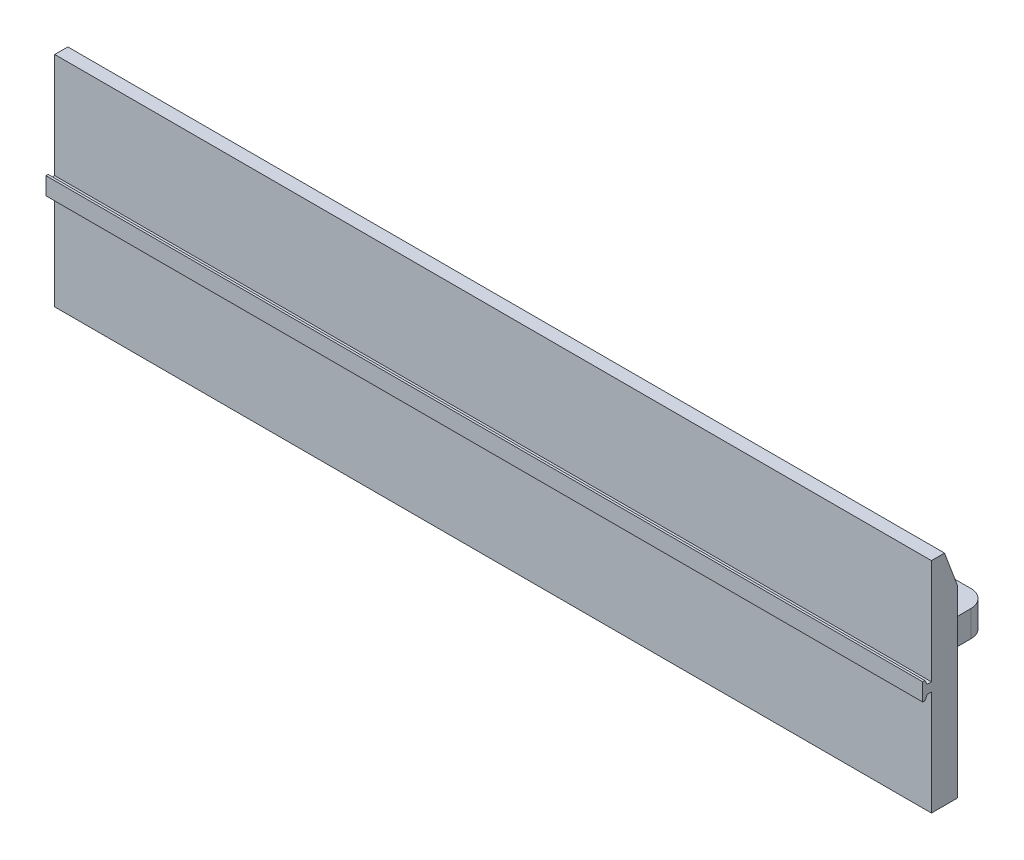
SolidWorks part; units mm, degrees
ref_plane "前视基准面" through (0, 0, 0) normal (0, 0, 1) x (1, 0, 0)
ref_plane "上视基准面" through (0, 0, 0) normal (0, 1, 0) x (1, 0, 0)
ref_plane "右视基准面" through (0, 0, 0) normal (1, 0, 0) x (0, 0, -1)
other "Configuration Table"
sketch "草图1" plane through (1027.5, 0, 0) normal (1, 0, 0) x (0, 0, -1)
  line L0 (-105, 300) -> (-105, 180)
  line L1 (-105, 180) -> (-110, 180)
  line L2 (-110, 180) -> (-112.5, 185)
  line L3 (-112.5, 185) -> (-115, 185)
  line L4 (-115, 185) -> (-115, 165)
  line L5 (-115, 165) -> (-112.5, 165)
  line L6 (-112.5, 165) -> (-110, 170)
  line L7 (-110, 170) -> (-105, 170)
  line L8 (-105, 170) -> (-105, 50)
  line L9 (-105, 300) -> (-90, 300)
  line L10 (-90, 300) -> (-75, 260)
  line L11 (-75, 260) -> (-75, 80)
  line L13 (-75, 50) -> (-105, 50)
  line L15 (-75, 50) -> (110, 50)
  line L17 (-75, 80) -> (110, 80)
  line L18 (110, 50) -> (110, 80)
extrude "凸台-拉伸1" add sketch "草图1" against normal blind 1002.5
sketch "草图2" plane through (0, 80, 0) normal (0, 1, 0) x (1, 0, 0)
  line L0 (25, -115) -> (1027.5, -115) construction
  line L1 (526.25, 145.125) -> (526.25, -305.1005) construction
  line L2 (25, 110) -> (1027.5, 110) construction
  line L3 (326.25, 110) -> (726.25, 110)
  line L4 (326.25, 110) -> (326.25, -75)
  line L5 (326.25, -75) -> (726.25, -75)
  line L6 (726.25, 110) -> (726.25, -75)
  line L7 (25, -75) -> (1027.5, -75) construction
  dimension "D1" = 200
  dimension "D2" = 200
extrude "切除-拉伸1" cut sketch "草图2" against normal through all both and the other way through all
sketch "草图3" plane through (0, 80, 0) normal (0, 1, 0) x (1, 0, 0)
  line L0 (25, -75) -> (1027.5, -75) construction
  line L1 (25, 110) -> (175, 110)
  line L2 (25, 110) -> (25, -75)
  line L3 (25, -75) -> (175, -75)
  line L4 (175, 110) -> (175, -75)
  line L5 (726.25, -75) -> (1027.5, -75) construction
  line L6 (1027.5, 110) -> (877.5, 110)
  line L7 (1027.5, 110) -> (1027.5, -75)
  line L8 (1027.5, -75) -> (877.5, -75)
  line L9 (877.5, 110) -> (877.5, -75)
  dimension "D1" = 150
  dimension "D2" = 150
extrude "切除-拉伸2" cut sketch "草图3" against normal through all both and the other way through all
ref_plane "基准面1" through (801.875, 0, 0) normal (1, 0, 0) x (0, 0, -1)
ref_plane "基准面2" through (250.625, 0, 0) normal (1, 0, 0) x (0, 0, -1)
sketch "草图4" plane through (801.875, 0, 0) normal (1, 0, 0) x (0, 0, -1)
  line L0 (-15, 80) -> (-75, 180)
  line L1 (110, 80) -> (-75, 80) construction
  line L2 (-75, 50) -> (-75, 260) construction
  dimension "D1" = 60
  dimension "D2" = 100
rib "筋1" sketch "草图4" sketch "草图4" thickness 20 extrusion direction parallel to sketch draft on no parameters "D1"=20
sketch "草图5" plane through (250.625, 0, 0) normal (1, 0, 0) x (0, 0, -1)
  line L0 (-75, 180) -> (-15, 80)
rib "筋2" sketch "草图5" sketch "草图5" thickness 20 extrusion direction parallel to sketch draft on no parameters "D1"=20
fillet "圆角2" radius 20 4 edges at (175, 65, -110) (326.25, 65, -110) (726.25, 65, -110) (877.5, 65, -110)
